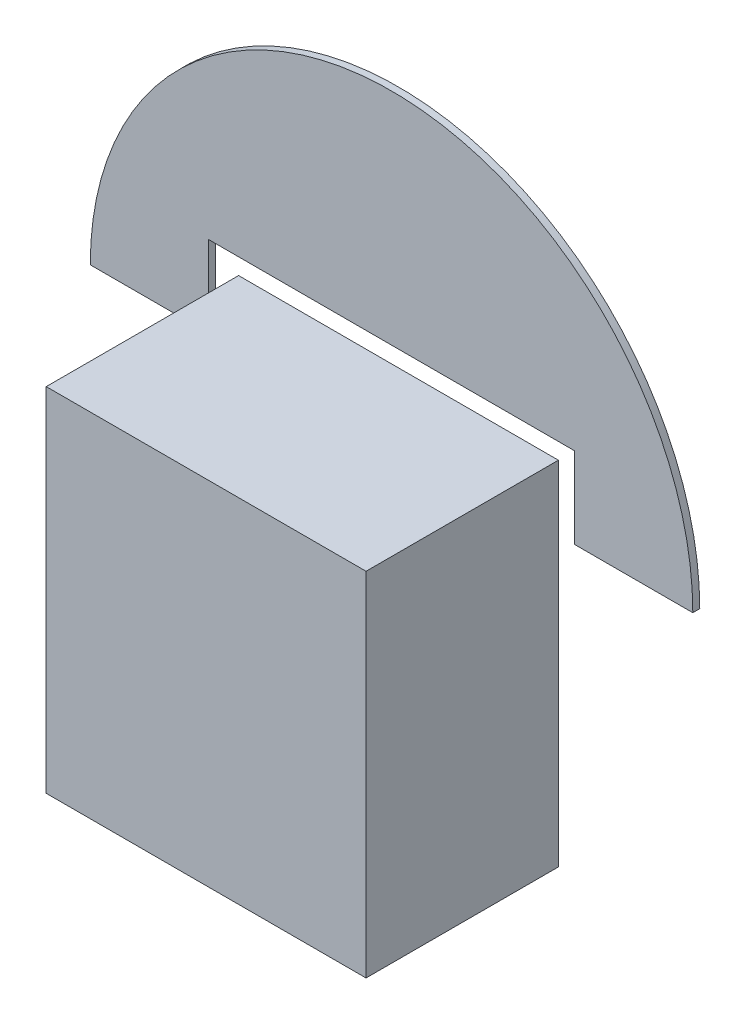
SolidWorks part; units mm, degrees
ref_plane "Front Plane" through (0, 0, 0) normal (0, 0, 1) x (1, 0, 0)
ref_plane "Top Plane" through (0, 0, 0) normal (0, 1, 0) x (1, 0, 0)
ref_plane "Right Plane" through (0, 0, 0) normal (1, 0, 0) x (0, 0, -1)
sketch "Sketch2" plane through (0, 0, 0) normal (0, 0, 1) x (1, 0, 0)
  line L0 (23.2626, 532.4408) -> (-1276.7374, 532.4408)
  line L1 (-666.7374, 782.4408) -> (713.2626, 782.4408)
  line L2 (-666.7374, 782.4408) -> (-666.7374, -737.5592)
  line L3 (-666.7374, -737.5592) -> (713.2626, -737.5592)
  line L4 (713.2626, 782.4408) -> (713.2626, -737.5592)
  line L5 (-766.7374, 882.4408) -> (813.2626, 882.4408)
  line L6 (-766.7374, 882.4408) -> (-766.7374, -837.5592)
  line L7 (-766.7374, -837.5592) -> (813.2626, -837.5592)
  line L8 (813.2626, 882.4408) -> (813.2626, -837.5592)
  line L9 (-1276.7374, 532.4408) -> (1323.2626, 532.4408)
  line L10 (23.2626, 1832.4408) -> (-926.7374, 882.4408)
  line L11 (-926.7374, 882.4408) -> (973.2626, 882.4408)
  line L12 (973.2626, 882.4408) -> (23.2626, 1832.4408)
  line L14 (520.278, 882.4408) -> (-590.1646, 882.4408)
  line L15 (-413.8893, 882.4408) -> (460.4144, 882.4408)
  line L16 (-413.8893, 882.4408) -> (-413.8893, 1756.7358)
  line L17 (-413.8893, 1756.7358) -> (460.4144, 1756.7358)
  line L18 (460.4144, 882.4408) -> (460.4144, 1756.7358)
  circle A0 centre (23.2626, 532.4408) radius 100
  circle A1 centre (23.2626, 532.4408) radius 1300
  dimension "D9" = 2600
  dimension "D12" = 200
  dimension "D1" = 1380
  dimension "D2" = 1520
  dimension "D3" = 100
  dimension "D4" = 100
  dimension "D5" = 100
  dimension "D6" = 100
  dimension "D7" = 250
  dimension "D8" = 690
  dimension "D11" = 45
  dimension "D14" = 874.295
  dimension "D15" = 874.3037
sketch "Sketch3" plane through (0, 0, 0) normal (0, 0, 1) x (1, 0, 0)
  line L0 (23.2626, 532.4408) -> (-1276.7374, 532.4408)
  line L1 (-666.7374, 782.4408) -> (713.2626, 782.4408)
  line L2 (-666.7374, 782.4408) -> (-666.7374, -737.5592)
  line L3 (-666.7374, -737.5592) -> (713.2626, -737.5592)
  line L4 (713.2626, 782.4408) -> (713.2626, -737.5592)
  line L5 (-766.7374, 882.4408) -> (813.2626, 882.4408)
  line L6 (-766.7374, 882.4408) -> (-766.7374, -837.5592)
  line L7 (-766.7374, -837.5592) -> (813.2626, -837.5592)
  line L8 (813.2626, 882.4408) -> (813.2626, -837.5592)
  line L9 (-1276.7374, 532.4408) -> (1323.2626, 532.4408)
  line L10 (23.2626, 1832.4408) -> (-926.7374, 882.4408)
  line L11 (-926.7374, 882.4408) -> (973.2626, 882.4408)
  line L12 (973.2626, 882.4408) -> (23.2626, 1832.4408)
  line L14 (520.278, 882.4408) -> (-590.1646, 882.4408)
  line L15 (-413.8893, 882.4408) -> (460.4144, 882.4408)
  line L16 (-413.8893, 882.4408) -> (-413.8893, 1756.7358)
  line L17 (-413.8893, 1756.7358) -> (460.4144, 1756.7358)
  line L18 (460.4144, 882.4408) -> (460.4144, 1756.7358)
  circle A0 centre (23.2626, 532.4408) radius 100
  circle A1 centre (23.2626, 532.4408) radius 1300
  dimension "D9" = 2600
  dimension "D12" = 200
  dimension "D1" = 1380
  dimension "D2" = 1520
  dimension "D3" = 100
  dimension "D4" = 100
  dimension "D5" = 100
  dimension "D6" = 100
  dimension "D7" = 250
  dimension "D8" = 690
  dimension "D11" = 45
  dimension "D14" = 874.295
  dimension "D15" = 874.3037
extrude "Boss-Extrude3" add sketch "Sketch2" along normal blind 830 contours L2 L3 L4 L1
extrude "Boss-Extrude4" add sketch "Sketch3" along normal blind 30 separate body contours L16 A1 L0 L6 L11 L10 | L17 L16 L10 | L10 A1 L17 | L12 L18 L17 | L17 A1 L12 | L9 A1 L18 L12 L11 L8
